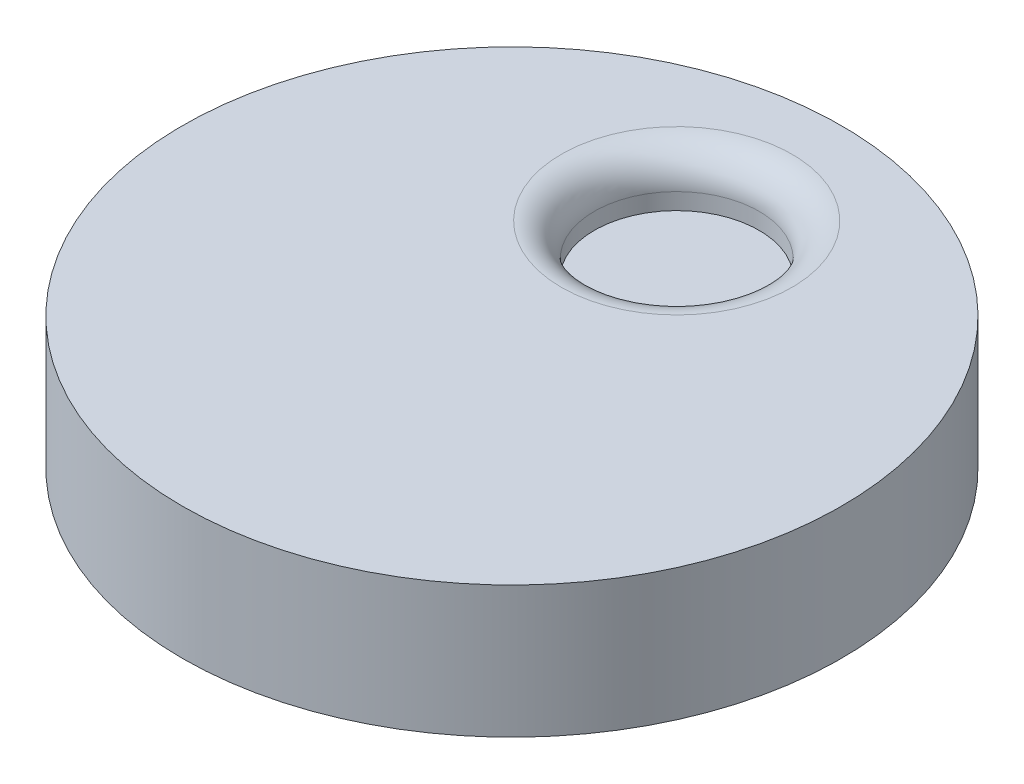
SolidWorks part; units mm, degrees
ref_plane "Alzado" through (0, 0, 0) normal (0, 0, 1) x (1, 0, 0)
ref_plane "Planta" through (0, 0, 0) normal (0, 1, 0) x (1, 0, 0)
ref_plane "Vista lateral" through (0, 0, 0) normal (1, 0, 0) x (0, 0, -1)
sketch "Croquis1" plane through (0, 0, 0) normal (0, 1, 0) x (1, 0, 0)
  circle A0 centre (0, 0) radius 20
  dimension "D1" = 40
extrude "Saliente-Extruir1" add sketch "Croquis1" along normal blind 8
sketch "Croquis2" plane through (0, 8, 0) normal (0, 1, 0) x (1, 0, 0)
  circle A0 centre (0, 10) radius 5
  dimension "D1" = 10
  dimension "D2" = 10
extrude "Cortar-Extruir1" cut sketch "Croquis2" against normal blind 3
fillet "Redondeo1" radius 2 1 edges at (0, 8, -5)
